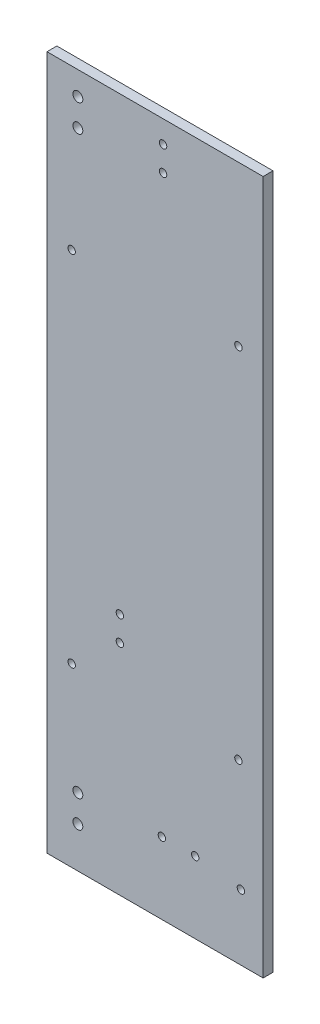
SolidWorks part; units mm, degrees
ref_plane "Plan de face" through (0, 0, 0) normal (0, 0, 1) x (1, 0, 0)
ref_plane "Plan de dessus" through (0, 0, 0) normal (0, 1, 0) x (1, 0, 0)
ref_plane "Plan de droite" through (0, 0, 0) normal (1, 0, 0) x (0, 0, -1)
sketch "Esquisse1" plane through (0, 0, 0) normal (0, 0, 1) x (1, 0, 0)
  line L0 (-7.0908, -30.3196) -> (-7.0908, -175.3196) construction
  line L1 (-17.0908, 34.1804) -> (70.4092, 34.1804)
  line L2 (-17.0908, 34.1804) -> (-17.0908, -246.8196)
  line L3 (-17.0908, -246.8196) -> (70.4092, -246.8196)
  line L4 (70.4092, 34.1804) -> (70.4092, -246.8196)
  line L5 (60.4092, -30.3196) -> (60.4092, -175.3196) construction
  line L6 (42.9092, -217.8196) -> (29.4092, -217.8196) construction
  line L7 (-4.5908, 24.6804) -> (-4.5908, 13.6804) construction
  line L8 (-4.5908, -219.3196) -> (-4.5908, -230.3196) construction
  line L9 (29.9092, 25.1804) -> (29.9092, 15.1804) construction
  line L10 (12.4092, -148.3196) -> (12.4092, -158.3196) construction
  circle A0 centre (-7.0908, -175.3196) radius 1.5
  circle A1 centre (-7.0908, -30.3196) radius 1.5
  circle A2 centre (60.4092, -30.3196) radius 1.5
  circle A3 centre (60.4092, -175.3196) radius 1.5
  circle A4 centre (42.9092, -217.8196) radius 1.5
  circle A5 centre (29.4092, -217.8196) radius 1.5
  circle A6 centre (61.4092, -220.3196) radius 1.5
  circle A7 centre (-4.5908, -219.3196) radius 2
  circle A8 centre (-4.5908, -230.3196) radius 2
  circle A9 centre (-4.5908, 24.6804) radius 2
  circle A10 centre (-4.5908, 13.6804) radius 2
  circle A11 centre (29.9092, 25.1804) radius 1.5
  circle A12 centre (29.9092, 15.1804) radius 1.5
  circle A13 centre (12.4092, -148.3196) radius 1.5
  circle A14 centre (12.4092, -158.3196) radius 1.5
  dimension "D6" = 10
  dimension "D9" = 13.5
  dimension "D12" = 26.5
  dimension "D14" = 11
  dimension "D17" = 12.5
  dimension "D20" = 9
  dimension "D23" = 10
  dimension "D1" = 87.5
  dimension "D2" = 281
  dimension "D3" = 10
  dimension "D4" = 64.5
  dimension "D5" = 71.5
  dimension "D7" = 64.5
  dimension "D8" = 71.5
  dimension "D10" = 27.5
  dimension "D11" = 29
  dimension "D13" = 9
  dimension "D15" = 16.5
  dimension "D16" = 12.5
  dimension "D18" = 11
  dimension "D19" = 9.5
  dimension "D21" = 10
  dimension "D22" = 47
  dimension "D24" = 29.5
  dimension "D25" = 88.5
extrude "Extrusion1" add sketch "Esquisse1" along normal blind 4
